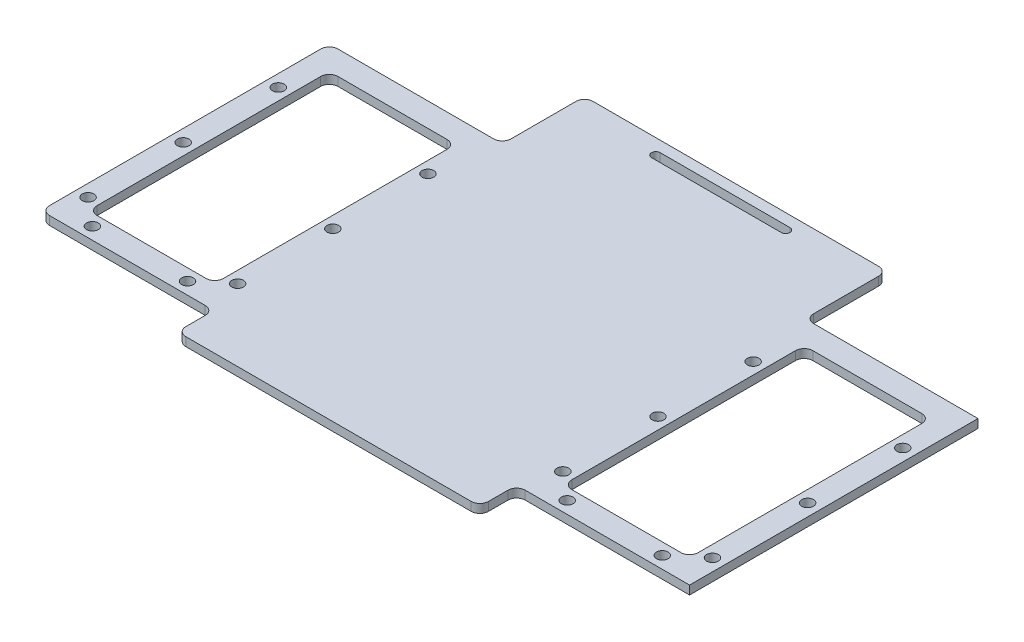
SolidWorks part; units mm, degrees
ref_plane "前视基准面" through (0, 0, 0) normal (0, 0, 1) x (1, 0, 0)
ref_plane "上视基准面" through (0, 0, 0) normal (0, 1, 0) x (1, 0, 0)
ref_plane "右视基准面" through (0, 0, 0) normal (1, 0, 0) x (0, 0, -1)
sketch "草图1" plane through (0, 0, 0) normal (0, 1, 0) x (1, 0, 0)
  line L0 (-35, -33.35) -> (-35, -41.85)
  line L1 (-75, 33.35) -> (-35, 33.35)
  line L2 (-75, 33.35) -> (-75, -33.35)
  line L3 (-75, -33.35) -> (-35, -33.35)
  line L4 (75, 33.35) -> (75, -33.35)
  line L5 (-75, 33.35) -> (75, -33.35) construction
  line L6 (-75, -33.35) -> (75, 33.35) construction
  line L7 (0, 42.1667) -> (0, -37.0897) construction
  line L8 (-69.5, 27.85) -> (-40.3, 27.85)
  line L9 (-69.5, 27.85) -> (-69.5, -27.85)
  line L10 (-69.5, -27.85) -> (-40.3, -27.85)
  line L11 (-40.3, 27.85) -> (-40.3, -27.85)
  line L12 (-69.5, 27.85) -> (-40.3, -27.85) construction
  line L13 (-69.5, -27.85) -> (-40.3, 27.85) construction
  line L14 (69.5, -27.85) -> (40.3, 27.85) construction
  line L15 (69.5, 27.85) -> (40.3, -27.85) construction
  line L16 (40.3, 27.85) -> (40.3, -27.85)
  line L17 (69.5, -27.85) -> (40.3, -27.85)
  line L18 (69.5, 27.85) -> (69.5, -27.85)
  line L19 (69.5, 27.85) -> (40.3, 27.85)
  line L20 (-54.9, -24.3068) -> (-54.9, 24.8269) construction
  line L21 (-35, 33.35) -> (-35, 52.35)
  line L22 (-35, 52.35) -> (35, 52.35)
  line L23 (35, 33.35) -> (35, 52.35)
  line L24 (35, 33.35) -> (75, 33.35)
  line L25 (-35, -41.85) -> (35, -41.85)
  line L26 (35, -33.35) -> (35, -41.85)
  line L27 (35, -33.35) -> (75, -33.35)
  line L29 (-15, 49.85) -> (15, 49.85)
  line L30 (-15, 49.85) -> (-15, 47.85) construction
  line L31 (-15, 47.85) -> (15, 47.85)
  line L32 (15, 49.85) -> (15, 47.85) construction
  line L33 (-15, 49.85) -> (15, 47.85) construction
  line L34 (-15, 47.85) -> (15, 49.85) construction
  circle A0 centre (-72.2, 18.75) radius 1.35
  circle A1 centre (-72.2, -3.25) radius 1.35
  circle A2 centre (-72.2, -25.25) radius 1.35
  circle A3 centre (-37.6, -25.25) radius 1.35
  circle A4 centre (-37.6, -3.25) radius 1.35
  circle A5 centre (-37.6, 18.75) radius 1.35
  circle A6 centre (37.6, 18.75) radius 1.35
  circle A7 centre (37.6, -3.25) radius 1.35
  circle A8 centre (37.6, -25.25) radius 1.35
  circle A9 centre (72.2, -25.25) radius 1.35
  circle A10 centre (72.2, -3.25) radius 1.35
  circle A11 centre (72.2, 18.75) radius 1.35
  arc A12 (-15, 49.85) -> (-15, 47.85) centre (-15, 48.85) ccw
  arc A13 (15, 47.85) -> (15, 49.85) centre (15, 48.85) ccw
  circle A14 centre (-43.9, -30.55) radius 1.35
  circle A15 centre (-65.9, -30.55) radius 1.35
  circle A16 centre (43.9, -30.55) radius 1.35
  circle A17 centre (65.9, -30.55) radius 1.35
  point P6 (0, 0)
  point P7 (0, 48.85)
  point P8 (-54.9, 0)
  point P19 (54.9, 0)
  point P49 (0, 52.35)
  point P57 (0, -41.85)
  dimension "D6" = 2.7
  dimension "D13" = 2
  dimension "D19" = 2.7
  dimension "D1" = 66.7
  dimension "D2" = 150
  dimension "D3" = 29.2
  dimension "D4" = 55.7
  dimension "D5" = 5.5
  dimension "D7" = 17.3
  dimension "D8" = 9.1
  dimension "D11" = 5.5
  dimension "D10" = 19
  dimension "D9" = 3
  dimension "D12" = 70
  dimension "D14" = 2.5
  dimension "D15" = 30
  dimension "D16" = 8.5
  dimension "D17" = 70
  dimension "D18" = 2.7
  dimension "D20" = 11
extrude "凸台-拉伸1" add sketch "草图1" along normal blind 2
fillet "圆角1" radius 2 18 edges at (69.5, 1, -27.85) (40.3, 1, 27.85) (69.5, 1, 27.85) (40.3, 1, -27.85) (-40.3, 1, 27.85) (-40.3, 1, -27.85) (-69.5, 1, -27.85) (-69.5, 1, 27.85) (-75, 1, -33.35) (-75, 1, 33.35) (35, 1, -52.35) (35, 1, -33.35) (-35, 1, -52.35) (-35, 1, -33.35) (35, 1, 33.35) (35, 1, 41.85) (-35, 1, 33.35) (-35, 1, 41.85)
